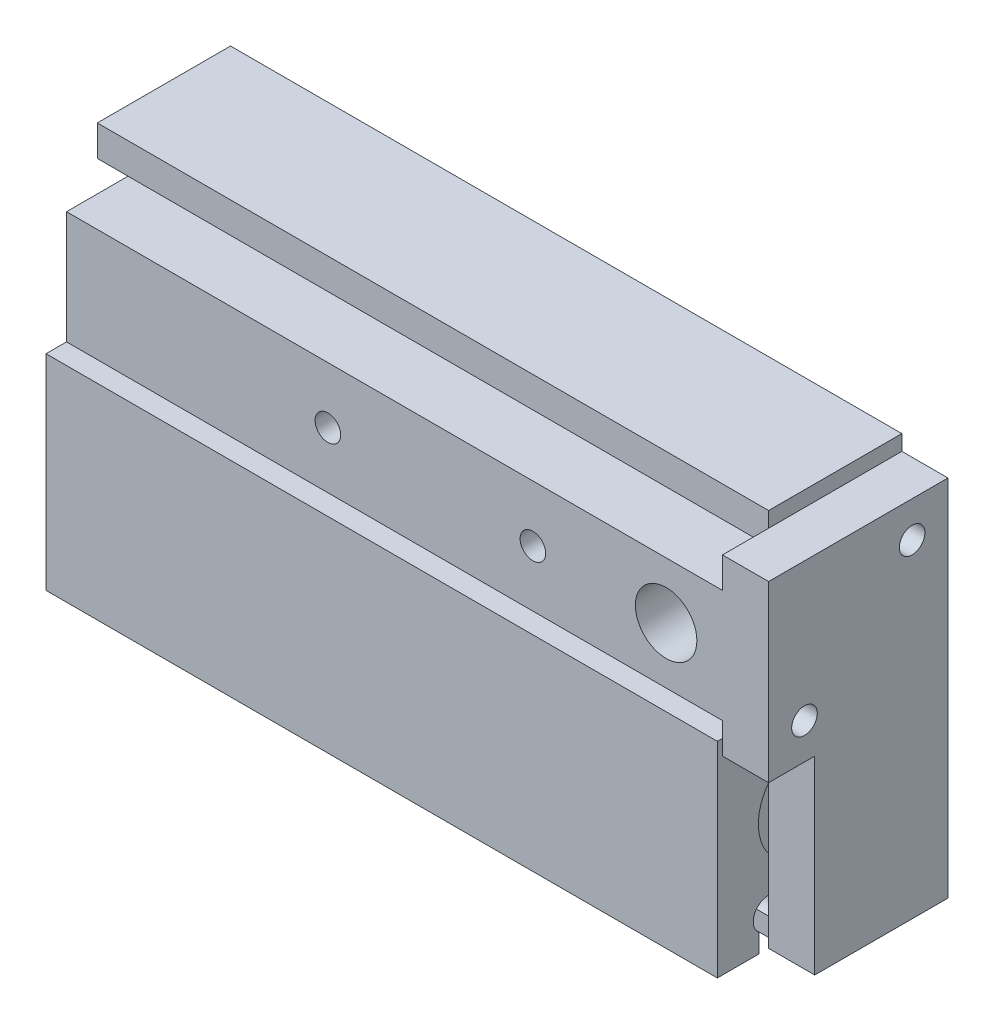
SolidWorks part; units mm, degrees
ref_plane "前视基准面" through (0, 0, 0) normal (0, 0, 1) x (1, 0, 0)
ref_plane "上视基准面" through (0, 0, 0) normal (0, 1, 0) x (1, 0, 0)
ref_plane "右视基准面" through (0, 0, 0) normal (1, 0, 0) x (0, 0, -1)
sketch "草图1" plane through (0, 0, 0) normal (1, 0, 0) x (0, 0, -1)
  line L1 (0, 0) -> (18, 0)
  line L2 (0, 0) -> (0, 37)
  line L3 (0, 37) -> (18, 37)
  line L4 (18, 0) -> (18, 37)
  dimension "D1" = 18
  dimension "D2" = 37
extrude "凸台-拉伸1" add sketch "草图1" along normal blind 65.5
sketch "草图2" plane through (0, 0, 0) normal (-1, 0, 0) x (0, 0, 1)
  line L0 (-9, 0) -> (-9, 18.5569) construction
  line L1 (0, 0) -> (-18, 0) construction
  circle A0 centre (-9, 11) radius 5
  dimension "D1" = 10
  dimension "D2" = 11
extrude "切除-拉伸1" cut sketch "草图2" against normal blind 0.5
sketch "草图3" plane through (65.5, 0, 0) normal (1, 0, 0) x (0, 0, -1)
  line L0 (9, 0) -> (9, 21.4556) construction
  line L1 (0, 0) -> (18, 0) construction
  circle A0 centre (9, 11) radius 5
  dimension "D1" = 10
  dimension "D2" = 11
extrude "切除-拉伸2" cut sketch "草图3" against normal blind 0.5
sketch "草图4" plane through (0, 0, 0) normal (-1, 0, 0) x (0, 0, 1)
  line L0 (-9, 0) -> (-9, 5.0998) construction
  line L1 (0, 0) -> (-18, 0) construction
  circle A0 centre (-13, 3) radius 1.5
  circle A1 centre (-5, 3) radius 1.5
  dimension "D1" = 3
  dimension "D2" = 8
  dimension "D3" = 3
extrude "切除-拉伸3" cut sketch "草图4" against normal through all
sketch "草图5" plane through (0, 0, 0) normal (-1, 0, 0) x (0, 0, 1)
  line L1 (0, 0) -> (-18, 0) construction
  line L2 (-13.9177, 0) -> (-12.0823, 0)
  line L3 (-13.9177, 0) -> (-13.9177, 2.7565)
  line L4 (-13.9177, 2.7565) -> (-12.0823, 2.7565)
  line L5 (-12.0823, 0) -> (-12.0823, 2.7565)
  line L6 (-9, 0) -> (-9, 3.3444) construction
  line L7 (-5.9177, 0) -> (-5.9177, 2.7565)
  line L8 (-4.0823, 2.7565) -> (-5.9177, 2.7565)
  line L9 (-4.0823, 0) -> (-4.0823, 2.7565)
  line L10 (-4.0823, 0) -> (-5.9177, 0)
  line L11 (-13, 2.7565) -> (-13, 0) construction
  line L12 (-5, 2.7565) -> (-5, 0) construction
  dimension "D1" = 8
extrude "切除-拉伸4" cut sketch "草图5" against normal through all
sketch "草图6" plane through (0, 0, 0) normal (-1, 0, 0) x (0, 0, 1)
  line L1 (0, 37) -> (-5, 37)
  line L2 (0, 37) -> (0, 20)
  line L3 (0, 20) -> (-5, 20)
  line L4 (-5, 37) -> (-5, 20)
  dimension "D1" = 5
  dimension "D2" = 17
extrude "切除-拉伸5" cut sketch "草图6" against normal through all
sketch "草图7" plane through (0, 0, 0) normal (-1, 0, 0) x (0, 0, 1)
  line L0 (-5, 37) -> (-5, 20) construction
  line L1 (-5, 34) -> (-13, 34)
  line L2 (-5, 34) -> (-5, 22)
  line L3 (-5, 22) -> (-13, 22)
  line L4 (-13, 34) -> (-13, 22)
  line L5 (-5, 28) -> (-13, 28) construction
  circle A0 centre (-9, 11) radius 5 construction
  dimension "D1" = 17
  dimension "D2" = 12
  dimension "D3" = 8
extrude "切除-拉伸6" cut sketch "草图7" against normal through all
sketch "草图8" plane through (65, 0, 0) normal (1, 0, 0) x (0, 0, -1)
  circle A0 centre (9, 11) radius 2.5
  dimension "D1" = 5
extrude "凸台-拉伸2" add sketch "草图8" along normal blind 1.5
sketch "草图9" plane through (66.5, 0, 0) normal (1, 0, 0) x (0, 0, -1)
  line L0 (18, 0) -> (18, 37) construction
  line L1 (17, 36.5) -> (-0.5, 36.5)
  line L2 (17, 36.5) -> (17, 1)
  line L3 (17, 1) -> (-0.5, 1)
  line L4 (-0.5, 36.5) -> (-0.5, 1)
  line L5 (18, 37) -> (5, 37) construction
  dimension "D1" = 1
  dimension "D2" = 0.5
  dimension "D3" = 35.5
  dimension "D4" = 17.5
extrude "凸台-拉伸3" add sketch "草图9" along normal blind 4.5
sketch "草图10" plane through (66.5, 0, 0) normal (-1, 0, 0) x (0, 0, 1)
  line L0 (0.5, 36.5) -> (0.5, 1) construction
  line L1 (-6.5, 33.5) -> (0.5, 33.5)
  line L2 (-6.5, 33.5) -> (-6.5, 22.5)
  line L3 (-6.5, 22.5) -> (0.5, 22.5)
  line L4 (0.5, 33.5) -> (0.5, 22.5)
  line L5 (-5, 34) -> (-13, 34) construction
  line L6 (-13, 22) -> (-5, 22) construction
  dimension "D1" = 0.5
  dimension "D2" = 0.5
  dimension "D3" = 7
extrude "凸台-拉伸4" add sketch "草图10" along normal blind 64
sketch "草图11" plane through (71, 0, 0) normal (1, 0, 0) x (0, 0, -1)
  line L0 (-0.5, 36.5) -> (-0.5, 1) construction
  line L1 (-0.5, 19.5) -> (4, 19.5)
  line L2 (-0.5, 19.5) -> (-0.5, 1)
  line L3 (-0.5, 1) -> (4, 1)
  line L4 (4, 19.5) -> (4, 1)
  line L5 (-0.5, 1) -> (17, 1) construction
  line L6 (17, 36.5) -> (-0.5, 36.5) construction
  dimension "D1" = 17
  dimension "D2" = 4.5
extrude "切除-拉伸7" cut sketch "草图11" against normal up to next
hole_wizard "M3 螺纹孔1" positions "草图13" profile "草图12" tap size "M3" standard "ISO"
sketch "草图13" plane through (71, 0, 0) normal (1, 0, 0) x (0, 0, -1)
  line L0 (18, 0) -> (18, 37) construction
  line L1 (18, 37) -> (5, 37) construction
  point P0 (13.5, 33)
  point P1 (3, 23)
  dimension "D1" = 4.5
  dimension "D2" = 4
  dimension "D3" = 10.5
  dimension "D4" = 10
sketch "草图12" plane through (71, 33, -13.5) normal (0, 1, 0) x (0, 0, -1)
  line L0 (0, 0) -> (0, 8.2511)
  line L1 (0, 8.2511) -> (1.25, 7.5)
  line L2 (1.25, 7.5) -> (1.25, 0)
  line L5 (1.25, 0) -> (0, 0)
  line L10 (0, 8.2511) -> (-1.25, 7.5) construction
  line L11 (0, -6.35) -> (0, 107.95) construction
  dimension "螺纹孔钻头直径" = 2.5
  dimension "螺纹孔钻头深度" = 7.5
  dimension "导头角度" = 118
cosmetic thread "孔螺蚊线1" parameters "D1"=6, "D2"=3
cosmetic thread "孔螺蚊线2" parameters "D1"=6, "D2"=3
hole_wizard "M3 六角凹头螺钉的柱形沉头孔1" positions "草图15" profile "草图14" counterbore size "M3" standard "ISO"
sketch "草图15" plane through (0, 0, -13) normal (0, 0, 1) x (1, 0, 0)
  line L0 (0, 28) -> (56.5837, 28) construction
  line L1 (0, 34) -> (0, 22) construction
  line L2 (65.5, 31.8544) -> (65.5, 22) construction
  point P0 (4, 28)
  point P2 (61.5, 28)
  dimension "D1" = 4
  dimension "D2" = 4
sketch "草图14" plane through (4, 28, -13) normal (1, 0, 0) x (0, -1, 0)
  line L0 (0, 0) -> (0, 5)
  line L1 (0, 5) -> (1.7, 5)
  line L3 (1.7, 5) -> (1.7, 3)
  line L4 (1.7, 3) -> (3.25, 3)
  line L5 (3.25, 3) -> (3.25, 0)
  line L7 (3.25, 0) -> (0, 0)
  line L11 (0, -6.35) -> (0, 107.95) construction
  dimension "通孔孔直径" = 3.4
  dimension "通孔孔深度" = 5
  dimension "柱形沉头孔直径" = 6.5
  dimension "柱形沉头孔深度" = 3
sketch "草图16" plane through (0, 0, 0.5) normal (0, 0, 1) x (1, 0, 0)
  line L0 (2.5, 28) -> (53.798, 28) construction
  line L1 (2.5, 22.5) -> (2.5, 33.5) construction
  line L2 (71, 36.5) -> (71, 19.5) construction
  circle A0 centre (61, 28) radius 3
  dimension "D1" = 6
  dimension "D2" = 10
extrude "切除-拉伸8" cut sketch "草图16" against normal up to next
hole_wizard "M3 螺纹孔2" positions "草图18" profile "草图17" tap size "M3" standard "ISO"
sketch "草图18" plane through (0, 0, 0.5) normal (0, 0, 1) x (1, 0, 0)
  line L0 (57.103, 28) -> (11.2511, 28) construction
  line L1 (71, 36.5) -> (71, 19.5) construction
  point P0 (28, 28)
  point P1 (48, 28)
  dimension "D1" = 23
  dimension "D2" = 20
sketch "草图17" plane through (28, 28, 0.5) normal (1, 0, 0) x (0, -1, 0)
  line L0 (0, 0) -> (0, 8.2511)
  line L1 (0, 8.2511) -> (1.25, 7.5)
  line L2 (1.25, 7.5) -> (1.25, 0)
  line L5 (1.25, 0) -> (0, 0)
  line L10 (0, 8.2511) -> (-1.25, 7.5) construction
  line L11 (0, -6.35) -> (0, 107.95) construction
  dimension "螺纹孔钻头直径" = 2.5
  dimension "螺纹孔钻头深度" = 7.5
  dimension "导头角度" = 118
cosmetic thread "孔螺蚊线3" parameters "D1"=6, "D2"=3
cosmetic thread "孔螺蚊线4" parameters "D1"=6, "D2"=3
